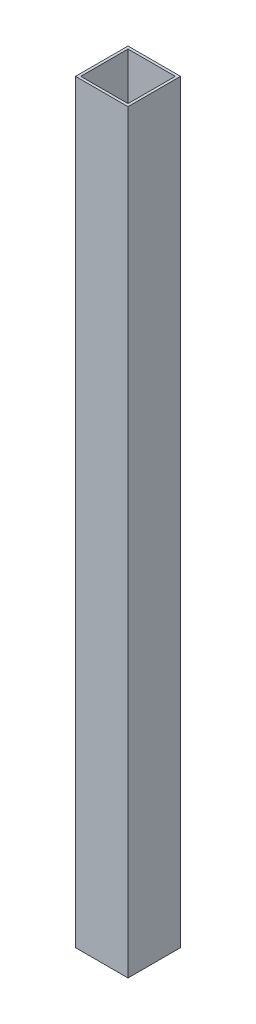
SolidWorks part; units mm, degrees
ref_plane "Front Plane" through (0, 0, 0) normal (0, 0, 1) x (1, 0, 0)
ref_plane "Top Plane" through (0, 0, 0) normal (0, 1, 0) x (1, 0, 0)
ref_plane "Right Plane" through (0, 0, 0) normal (1, 0, 0) x (0, 0, -1)
sketch "Sketch1" plane through (0, 0, 0) normal (0, 1, 0) x (1, 0, 0)
  line L1 (10, 10) -> (-10, 10)
  line L2 (10, 10) -> (10, -10)
  line L3 (10, -10) -> (-10, -10)
  line L4 (-10, 10) -> (-10, -10)
  line L5 (10, 10) -> (-10, -10) construction
  line L6 (10, -10) -> (-10, 10) construction
  line L7 (9, 9) -> (-9, 9)
  line L8 (9, 9) -> (9, -9)
  line L9 (9, -9) -> (-9, -9)
  line L10 (-9, 9) -> (-9, -9)
  line L11 (9, 9) -> (-9, -9) construction
  line L12 (9, -9) -> (-9, 9) construction
  point P0 (0, 0)
  point P6 (0, 0)
  dimension "D1" = 20
  dimension "D2" = 20
  dimension "D3" = 18
  dimension "D4" = 18
extrude "Boss-Extrude1" add sketch "Sketch1" along normal blind 287.33
